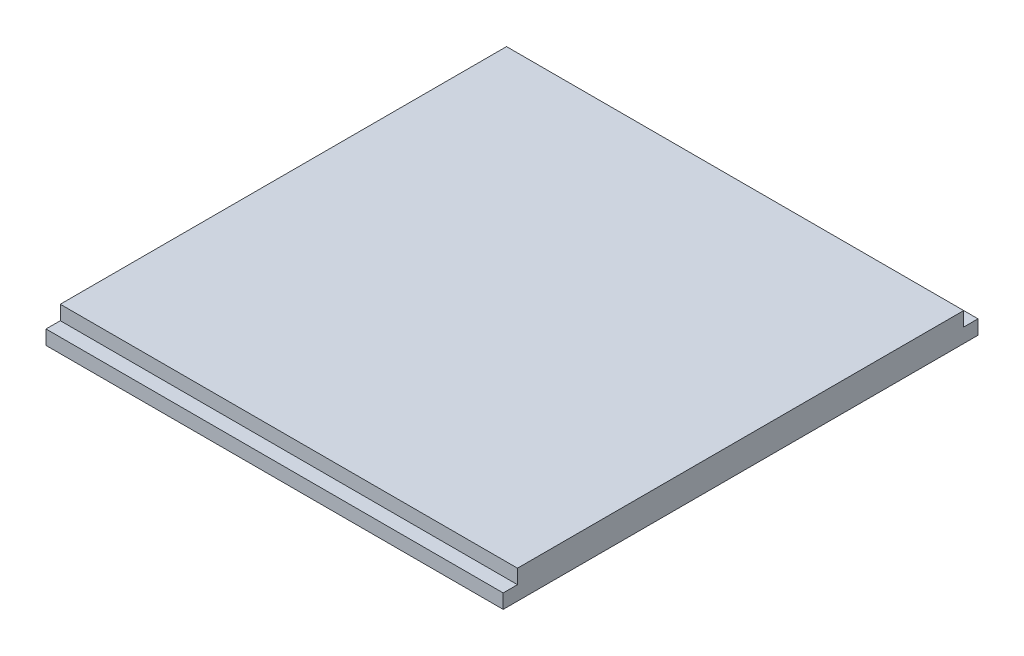
SolidWorks part; units mm, degrees
ref_plane "Front Plane" through (0, 0, 0) normal (0, 0, 1) x (1, 0, 0)
ref_plane "Top Plane" through (0, 0, 0) normal (0, 1, 0) x (1, 0, 0)
ref_plane "Right Plane" through (0, 0, 0) normal (1, 0, 0) x (0, 0, -1)
sketch "Sketch1" plane through (0, 0, 0) normal (0, 1, 0) x (1, 0, 0)
  line L1 (960, 997) -> (-960, 997)
  line L2 (960, 997) -> (960, -997)
  line L3 (960, -997) -> (-960, -997)
  line L4 (-960, 997) -> (-960, -997)
  line L5 (960, 997) -> (-960, -997) construction
  line L6 (960, -997) -> (-960, 997) construction
  point P0 (0, 0)
  dimension "D1" = 1994
  dimension "D2" = 1920
extrude "Boss-Extrude1" add sketch "Sketch1" along normal blind 120
ref_plane "Plane1" through (-960, 0, 0) normal (-1, 0, 0) x (0, 0, 1)
sketch "Sketch2" plane through (-960, 0, 0) normal (-1, 0, 0) x (0, 0, 1)
  line L0 (-997, 120) -> (997, 120) construction
  line L25 (-997, 120) -> (-937, 120)
  line L26 (-997, 120) -> (-997, 60)
  line L27 (937, 0) -> (937, 60)
  line L28 (-937, 60) -> (-937, 0)
  line L29 (937, 60) -> (-937, 60)
  line L30 (937, 0) -> (937, 60) construction
  line L31 (-937, 60) -> (-937, 0) construction
  line L32 (937, 60) -> (-937, 60) construction
  line L33 (-997, 60) -> (-937, 60)
  line L34 (-937, 120) -> (-937, 60)
  line L35 (997, 120) -> (937, 120)
  line L36 (997, 120) -> (997, 60)
  line L37 (997, 60) -> (937, 60)
  line L38 (937, 120) -> (937, 60)
  dimension "D2" = 60
  dimension "D1" = 60
extrude "Cut-Extrude1" cut sketch "Sketch2" against normal through all
